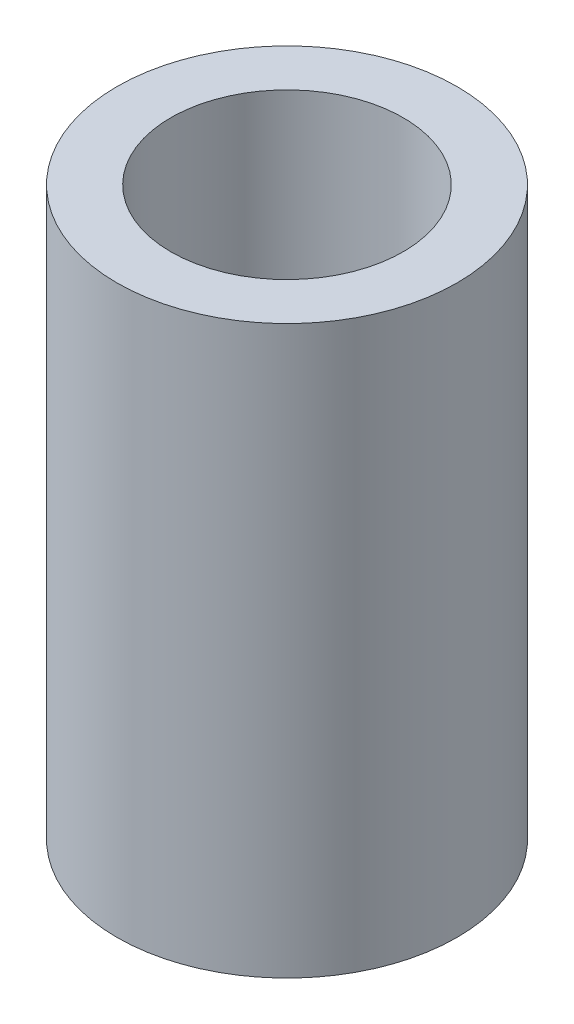
SolidWorks part; units mm, degrees
ref_plane "Front Plane" through (0, 0, 0) normal (0, 0, 1) x (1, 0, 0)
ref_plane "Top Plane" through (0, 0, 0) normal (0, 1, 0) x (1, 0, 0)
ref_plane "Right Plane" through (0, 0, 0) normal (1, 0, 0) x (0, 0, -1)
ref_plane "Plane1" through (0, 470, 0) normal (0, 1, 0) x (1, 0, 0)
sketch "Sketch1" plane through (0, 470, 0) normal (0, 1, 0) x (1, 0, 0)
  circle A0 centre (300, -157) radius 6
extrude "Boss-Extrude1" add sketch "Sketch1" along normal blind 20
sketch "Sketch2" plane through (0, 490, 0) normal (0, 1, 0) x (1, 0, 0)
  circle A0 centre (300, -157) radius 4.1
extrude "Cut-Extrude1" cut sketch "Sketch2" against normal blind 40
